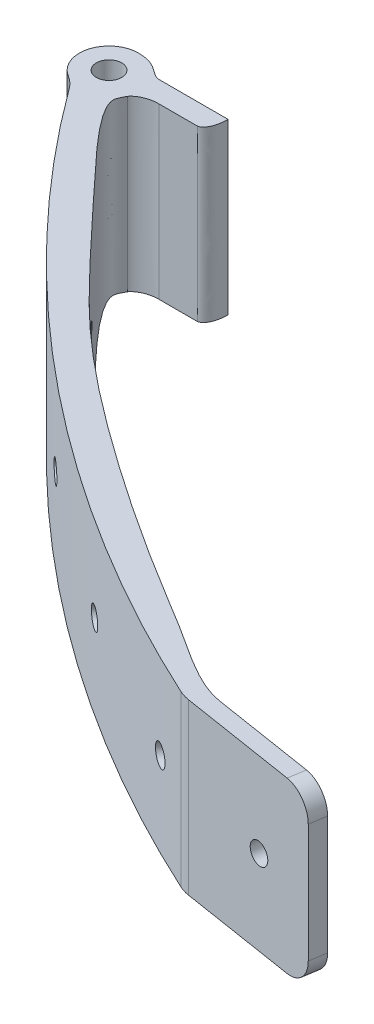
SolidWorks part; units mm, degrees
ref_plane "Спереди" through (0, 0, 0) normal (0, 0, 1) x (1, 0, 0)
ref_plane "Сверху" through (0, 0, 0) normal (0, 1, 0) x (1, 0, 0)
ref_plane "Справа" through (0, 0, 0) normal (1, 0, 0) x (0, 0, -1)
sketch "Эскиз1" plane through (0, 0, 0) normal (0, 1, 0) x (1, 0, 0)
  line L0 (0, 0) -> (63.6396, 63.6396) construction
  line L1 (63.6396, 63.6396) -> (77.7817, 49.4975) construction
  line L2 (77.7817, 49.4975) -> (14.1421, -14.1421) construction
  line L3 (14.1421, -14.1421) -> (0, 0) construction
  line L4 (7.0711, -7.0711) -> (14.1421, 0) construction
  line L6 (77.202, -81.2231) -> (93.9927, -83.8825)
  line L7 (70.8671, -77.0244) -> (8.0709, -21.5) construction
  line L8 (12.1432, -19.5) -> (20.1432, -19.5)
  line L9 (70.7107, 56.5685) -> (63.6396, 49.4975) construction
  line L10 (94.3055, -81.9072) -> (79.4902, -79.5606)
  line L11 (27.5417, -48.2722) -> (29.9443, -45.727) construction
  line L12 (14.1587, -34.0951) -> (16.8404, -31.8461) construction
  line L13 (48.9131, -65.4993) -> (50.894, -62.6138) construction
  line L14 (93.9927, -83.8825) -> (94.3055, -81.9072)
  line L16 (66.723, -76.2847) -> (68.1288, -73.6345) construction
  line L17 (18.9974, -22) -> (14.4974, -22)
  line L20 (5.6959, -21.5) -> (5.6959, -21.1413)
  line L23 (4.5709, -21.5) -> (4.5709, -2.8969) construction
  circle A0 centre (14.1421, 0) radius 10 construction
  circle A1 centre (14.1421, 0) radius 18 construction
  arc A2 (8.0709, -18) -> (6.2308, -24.4772) centre (8.0709, -21.5) ccw
  circle A4 centre (8.0709, -21.5) radius 1.5
  arc A6 (75.8905, -80.8253) -> (77.202, -81.2231) centre (77.9841, -76.2847) ccw
  arc A7 (79.4902, -79.5606) -> (76.7541, -79.1041) centre (78.9127, -74.5941) cw construction
  arc A8 (6.2308, -24.4772) -> (7.6373, -25.778) centre (3.602, -28.7304) cw
  circle A9 centre (63.6396, 49.4975) radius 10
  circle A10 centre (63.6396, 49.4975) radius 16 construction
  circle A11 centre (8.0709, -21.5) radius 3.5 construction
  ellipse E0 centre (124.1604, 27.5696) end of major axis (257.4039, -40.3213) minor radius 117.3887 construction
  ellipse E1 centre (125.5237, 27.2385) end of major axis (259.888, -41.2235) minor radius 116.9528 (12.425, -28.8564) -> (76.7541, -79.1041) ccw construction
  ellipse E2 centre (123.0354, 27.5696) end of major axis (254.35, -39.3385) minor radius 118.1251 (7.6373, -25.778) -> (75.8905, -80.8253) ccw
  spline S0 degree 3 poles (79.4902, -79.5606) (76.2568, -79.1543) (71.6563, -75.7337) (61.067, -69.4038) (49.7791, -62.0875) (36.2715, -52.166) (26.1525, -41.8799) (21.2755, -36.5993) (15.1219, -30.0137) (10.6985, -24.9313) (11.5239, -23.7007) (11.8471, -23.0721) knots 0 0 0 0 0.116955 0.152933 0.359777 0.631849 0.683688 0.856553 0.887566 0.97221 1 1 1 1
  spline S1 degree 3 poles (11.8471, -23.0721) (12.2501, -22.5154) (13.3113, -21.9714) (14.4974, -22) knots 0 0 0 0 1 1 1 1
  spline S2 degree 3 poles (8.0709, -18) (10.5942, -18.0229) (10.9113, -19.5495) (12.1432, -19.5) knots 0 0 0 0 1 1 1 1
  spline S3 degree 3 poles (20.1432, -19.5) (20.1266, -21.365) (19.3697, -21.9934) (18.9974, -22) knots 0 0 0 0 1 1 1 1
  point P72 (10.9432, -19.5)
  dimension "D1" = 7
  dimension "D2" = 8
  dimension "D4" = 5
  dimension "D5" = 5
  dimension "D6" = 5
extrude "Бобышка-Вытянуть1" add sketch "Эскиз1" along normal blind 20
sketch "Эскиз2" plane through (-10.3475, 0, 65.3317) normal (0.1564, 0, -0.9877) x (-0.9877, 0, -0.1564)
  line L3 (-98.9576, 10) -> (-105.9576, 10) construction
  line L4 (-105.9576, 20) -> (-105.9576, 0) construction
  circle A0 centre (-98.9576, 10) radius 1.25
  dimension "D1" = 7
extrude "Вырез-Вытянуть1" cut sketch "Эскиз2" against normal through all
sketch "Эскиз3" plane through (0, 20, 0) normal (0, 1, 0) x (1, 0, 0)
  line L0 (76.1579, -78.8175) -> (71.7299, -76.4952)
  line L1 (71.7299, -76.4952) -> (72.4361, -75.1486)
  line L2 (71.7299, -76.4952) -> (54.3938, -66.5223)
  line L3 (55.1553, -65.3008) -> (53.2371, -68.3776)
  line L4 (54.3938, -66.5223) -> (37.4756, -54.0814)
  line L5 (37.4756, -54.0814) -> (39.716, -51.6828)
  line L6 (37.4756, -54.0814) -> (22.7691, -40.5271)
  line L7 (22.7691, -40.5271) -> (23.7775, -39.6631)
  ellipse E1 centre (123.0354, 27.5696) end of major axis (254.35, -39.3385) minor radius 118.1251 (7.6373, -25.778) -> (75.8905, -80.8253) ccw construction
  dimension "D1" = 5
  dimension "D2" = 20
  dimension "D3" = 21
  dimension "D4" = 20
ref_plane "Плоскость1" through (-15.9907, 0, 30.4907) normal (0.4644, 0, -0.8856) x (-0.8856, 0, -0.4644)
sketch "Эскиз5" plane through (-15.9907, 0, 30.4907) normal (0.4644, 0, -0.8856) x (-0.8856, 0, -0.4644)
  line L0 (-104.052, 20) -> (-104.052, 0) construction
  line L1 (-104.052, 0) -> (-104.052, 10) construction
  line L2 (-104.052, 10) -> (-99.552, 10) construction
  circle A0 centre (-99.552, 10) radius 1.25
  dimension "D1" = 4.5
extrude "Вырез-Вытянуть2" cut sketch "Эскиз5" against normal through all and the other way through all
ref_plane "Плоскость2" through (54.3938, 20, 66.5223) normal (-0.529, 0, 0.8486) x (0.8486, 0, 0.529)
sketch "Эскиз6" plane through (54.3938, 20, 66.5223) normal (-0.529, 0, 0.8486) x (0.8486, 0, 0.529)
  line L0 (0, 0) -> (0, -10) construction
  circle A0 centre (0, -10) radius 1.25
extrude "Вырез-Вытянуть3" cut sketch "Эскиз6" along normal through all from offset 5 offset against normal yes
ref_plane "Плоскость3" through (37.4756, 20, 54.0814) normal (0.6826, 0, -0.7308) x (-0.7308, 0, -0.6826)
sketch "Эскиз7" plane through (37.4756, 20, 54.0814) normal (0.6826, 0, -0.7308) x (-0.7308, 0, -0.6826)
  line L0 (0, 0) -> (0, -10) construction
  line L1 (-20.8558, 0) -> (0, 0) construction
  circle A0 centre (0, -10) radius 1.25
extrude "Вырез-Вытянуть5" cut sketch "Эскиз7" against normal through all from offset 10
ref_plane "Плоскость4" through (22.7691, 20, 40.5271) normal (0.7594, 0, -0.6506) x (-0.6506, 0, -0.7594)
sketch "Эскиз8" plane through (22.7691, 20, 40.5271) normal (0.7594, 0, -0.6506) x (-0.6506, 0, -0.7594)
  line L0 (0, 0) -> (0, -10) construction
  line L1 (-19.8615, 0) -> (0, 0) construction
  circle A0 centre (0, -10) radius 1.25
extrude "Вырез-Вытянуть6" cut sketch "Эскиз8" against normal through all from offset 10
fillet "Скругление1" radius 3 2 edges at (94.1491, 0, 82.8948) (94.1491, 20, 82.8948)
